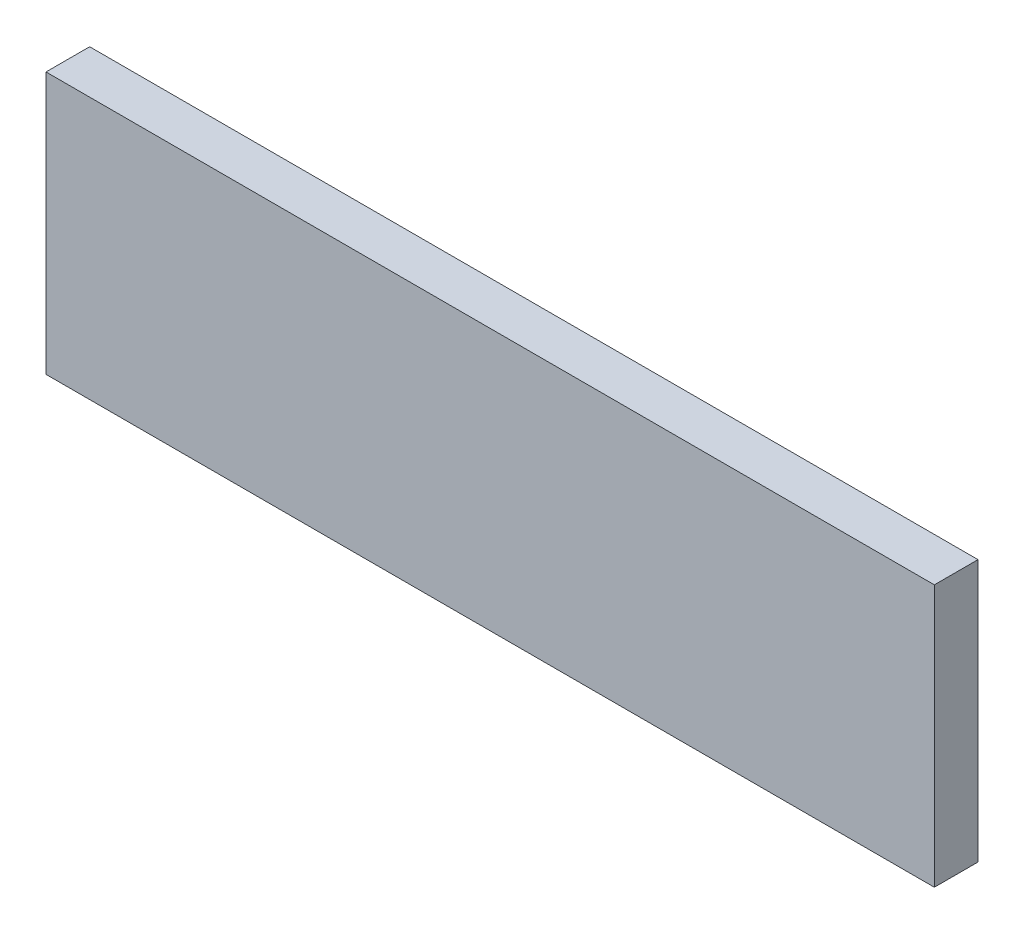
SolidWorks part; units mm, degrees
material "Pino"
ref_plane "Alzado" through (0, 0, 0) normal (0, 0, 1) x (1, 0, 0)
ref_plane "Planta" through (0, 0, 0) normal (0, 1, 0) x (1, 0, 0)
ref_plane "Vista lateral" through (0, 0, 0) normal (1, 0, 0) x (0, 0, -1)
sketch "Croquis1" plane through (0, 0, 0) normal (0, 0, 1) x (1, 0, 0)
  line L1 (-203.5, -60) -> (203.5, -60)
  line L2 (-203.5, -60) -> (-203.5, 60)
  line L3 (-203.5, 60) -> (203.5, 60)
  line L4 (203.5, -60) -> (203.5, 60)
  line L5 (-203.5, -60) -> (203.5, 60) construction
  line L6 (-203.5, 60) -> (203.5, -60) construction
  point P0 (0, 0)
  dimension "D1" = 407
  dimension "D2" = 120
extrude "Saliente-Extruir1" add sketch "Croquis1" along normal blind 20
